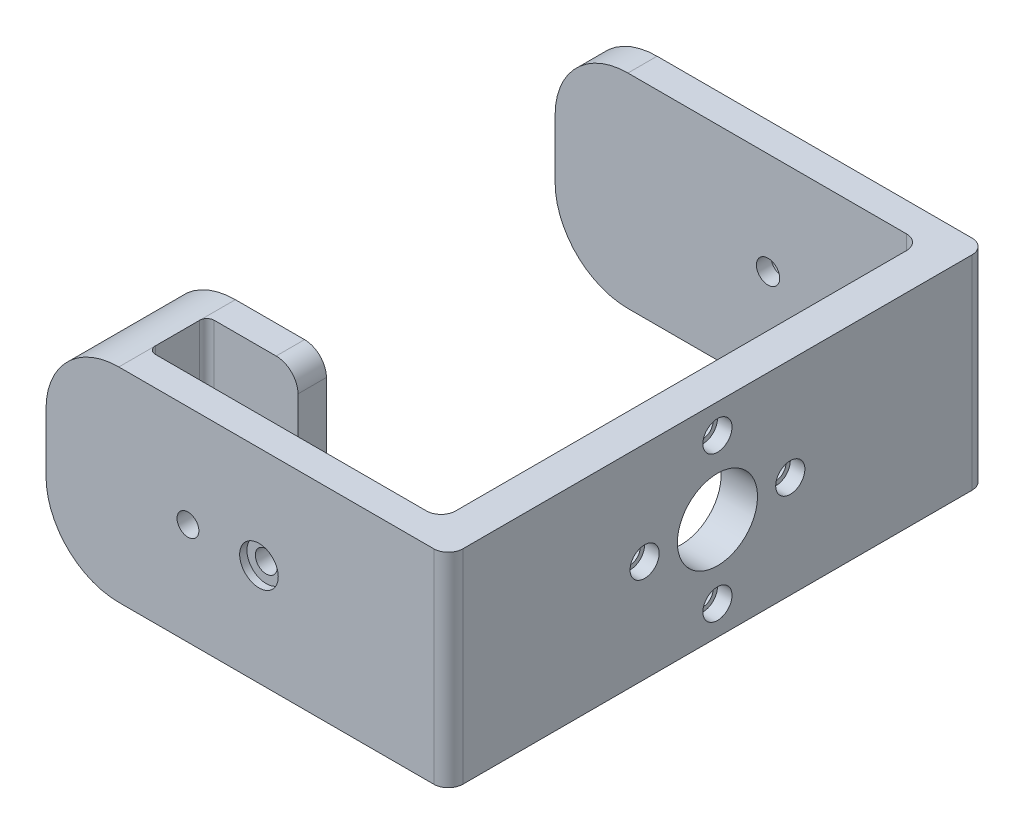
SolidWorks part; units mm, degrees
material "Esun Hard Tough Resin"
ref_plane "Front Plane" through (0, 0, 0) normal (0, 0, 1) x (1, 0, 0)
ref_plane "Top Plane" through (0, 0, 0) normal (0, 1, 0) x (1, 0, 0)
ref_plane "Right Plane" through (0, 0, 0) normal (1, 0, 0) x (0, 0, -1)
sketch "Sketch1" plane through (0, 0, 0) normal (0, 1, 0) x (1, 0, 0)
  line L1 (27.62, -36.95) -> (-27.62, -36.95)
  line L2 (27.62, -36.95) -> (27.62, 36.95)
  line L3 (27.62, 36.95) -> (-27.62, 36.95)
  line L4 (-27.62, -36.95) -> (-27.62, 36.95)
  line L5 (27.62, -36.95) -> (-27.62, 36.95) construction
  line L6 (27.62, 36.95) -> (-27.62, -36.95) construction
  line L7 (-27.62, 32.95) -> (22.62, 32.95)
  line L8 (-27.62, 32.95) -> (-27.62, -32.95)
  line L9 (-27.62, -32.95) -> (22.62, -32.95)
  line L10 (22.62, 32.95) -> (22.62, -32.95)
  point P0 (0, 0)
  point P10 (22.62, 0)
  dimension "D1" = 65.9
  dimension "D2" = 4
  dimension "D3" = 50.24
  dimension "D4" = 5
extrude "Boss-Extrude1" add sketch "Sketch1" along normal blind 28 contours L7 L10 L9 L4 L1 L2 L3
sketch "Sketch2" plane through (22.62, 0, 0) normal (-1, 0, 0) x (0, 0, 1)
  line L4 (-10, 14) -> (32.95, 14) construction
  line L6 (-7.0711, 21.0711) -> (7.0711, 6.9289) construction
  line L7 (32.95, 28) -> (32.95, 0) construction
  line L8 (7.0711, 21.0711) -> (-7.0711, 6.9289) construction
  circle A0 centre (0, 14) radius 10 construction
  circle A1 centre (0, 4) radius 1.4
  circle A2 centre (0, 24) radius 1.4
  circle A4 centre (-10, 14) radius 1.4
  circle A5 centre (10, 14) radius 1.4
  circle A8 centre (0, 14) radius 5.5
  point P2 (-19.7742, 14)
  point P4 (0, 0)
  point P6 (0, 28)
  dimension "D4" = 2.8
  dimension "D5" = 11
  dimension "D2" = 10
  dimension "D3" = 45
  dimension "D6" = 45
extrude "Cut-Extrude1" cut sketch "Sketch2" against normal through all
sketch "Sketch3" plane through (0, 0, 36.95) normal (0, 0, 1) x (1, 0, 0)
  line L0 (-27.62, 28) -> (-27.62, 0) construction
  line L1 (-8.38, 14) -> (11.62, 14) construction
  line L3 (1.62, 4) -> (1.62, 24) construction
  circle A0 centre (1.62, 14) radius 10 construction
  circle A1 centre (-8.38, 14) radius 1.4 construction
  circle A3 centre (1.62, 4) radius 1.4 construction
  circle A5 centre (11.62, 14) radius 1.4 construction
  circle A7 centre (1.62, 24) radius 1.4 construction
  circle A9 centre (1.62, 14) radius 1.5
  point P5 (-27.62, 14)
  dimension "D2" = 20
  dimension "D5" = 3
  dimension "D3" = 2.8
  dimension "D1" = 1.62
extrude "Cut-Extrude2" cut sketch "Sketch3" against normal up to next
sketch "Sketch4" plane through (0, 0, -36.95) normal (0, 0, -1) x (-1, 0, 0)
  line L0 (8.38, 14) -> (-11.62, 14) construction
  circle A0 centre (-1.62, 14) radius 1.6
  dimension "D1" = 3.2
extrude "Cut-Extrude3" cut sketch "Sketch4" against normal up to next
sketch "Sketch6" plane through (27.62, 0, 0) normal (1, 0, 0) x (0, 0, -1)
  circle A1 centre (0, 24) radius 2
  circle A4 centre (10, 14) radius 2
  circle A6 centre (0, 4) radius 2
  circle A8 centre (-10, 14) radius 2
  circle A12 centre (0, 24) radius 1.4 construction
  circle A14 centre (10, 14) radius 1.4 construction
  circle A16 centre (0, 4) radius 1.4 construction
  circle A18 centre (-10, 14) radius 1.4 construction
  dimension "D1" = 4
extrude "Cut-Extrude5" cut sketch "Sketch6" against normal blind 2
sketch "Sketch7" plane through (0, 0, -36.95) normal (0, 0, -1) x (-1, 0, 0)
  circle A0 centre (-1.62, 14) radius 2.65
  dimension "D1" = 5.3
extrude "Cut-Extrude6" cut sketch "Sketch7" against normal blind 2
fillet "Fillet1" radius 10 4 edges at (-27.62, 0, 34.95) (-27.62, 28, 34.95) (-27.62, 0, -34.95) (-27.62, 28, -34.95)
fillet "Fillet2" radius 2 4 edges at (27.62, 14, -36.95) (27.62, 14, 36.95) (22.62, 14, 32.95) (22.62, 14, -32.95)
sketch "Sketch9" plane through (0, 0, 32.95) normal (0, 0, -1) x (-1, 0, 0)
  line L0 (17.62, 28) -> (17.62, 0)
  line L4 (17.62, 28) -> (-20.62, 28)
  line L5 (-20.62, 28) -> (-20.62, 0)
  line L6 (-20.62, 0) -> (17.62, 0)
  line L7 (27.62, 10) -> (27.62, 18)
  line L11 (27.62, 10) -> (27.62, 18)
  arc A2 (17.62, 0) -> (27.62, 10) centre (17.62, 10) ccw
  arc A3 (27.62, 18) -> (17.62, 28) centre (17.62, 18) ccw
  arc A4 (17.62, 0) -> (27.62, 10) centre (17.62, 10) ccw
  arc A5 (27.62, 18) -> (17.62, 28) centre (17.62, 18) ccw
  point P9 (0, 0)
  dimension "D1" = 0
extrude "Boss-Extrude2" add sketch "Sketch9" along normal blind 12
sketch "Sketch10" plane through (-17.62, 0, 0) normal (1, 0, 0) x (0, 0, -1)
  line L1 (-24.85, 28) -> (-20.95, 28)
  line L2 (-24.85, 28) -> (-24.85, 0)
  line L3 (-24.85, 0) -> (-20.95, 0)
  line L4 (-20.95, 28) -> (-20.95, 0)
  line L5 (-34.95, 28) -> (34.95, 28) construction
  line L6 (-34.95, 0) -> (34.95, 0) construction
  line L7 (-20.95, 28) -> (-20.95, 0) construction
  point P7 (-20.677, 2.1944)
  dimension "D1" = 3.9
extrude "Boss-Extrude3" add sketch "Sketch10" along normal blind 12.5
sketch "Sketch8" plane through (0, 0, 36.95) normal (0, 0, 1) x (1, 0, 0)
  line L0 (-998.38, 14) -> (49001.62, 14) construction
  circle A0 centre (-8.13, 14) radius 1.5
  point P4 (1.62, 14)
  dimension "D2" = 3
  dimension "D1" = 9.75
extrude "Cut-Extrude8" cut sketch "Sketch8" against normal up to surface (16 mm away) up to face at (-17.477, 14, 20.95)
sketch "Sketch11" plane through (0, 0, 20.95) normal (0, 0, -1) x (-1, 0, 0)
  circle A0 centre (8.13, 14) radius 1.5 construction
  circle A1 centre (8.13, 14) radius 1.5
  circle A2 centre (8.13, 14) radius 2.75
  dimension "D1" = 5.5
extrude "Cut-Extrude9" cut sketch "Sketch11" against normal blind 1.5
fillet "Fillet3" radius 3 2 edges at (-5.12, 0, 22.9) (-5.12, 28, 22.9)
fillet "Fillet4" radius 1 2 edges at (-17.62, 14, 32.95) (-17.62, 14, 24.85)
sketch "Sketch12" plane through (0, 0, 36.95) normal (0, 0, 1) x (1, 0, 0)
  circle A0 centre (1.62, 14) radius 1.5 construction
  circle A1 centre (1.62, 14) radius 1.5
  circle A2 centre (1.62, 14) radius 2.65
  dimension "D1" = 5.3
extrude "Cut-Extrude10" cut sketch "Sketch12" against normal blind 1
equation "\"D1@Sketch8\"=(7.5mm/2)+(12mm/2)"
equation "\"D1@Sketch1\"=79.000000mm-13.1"
